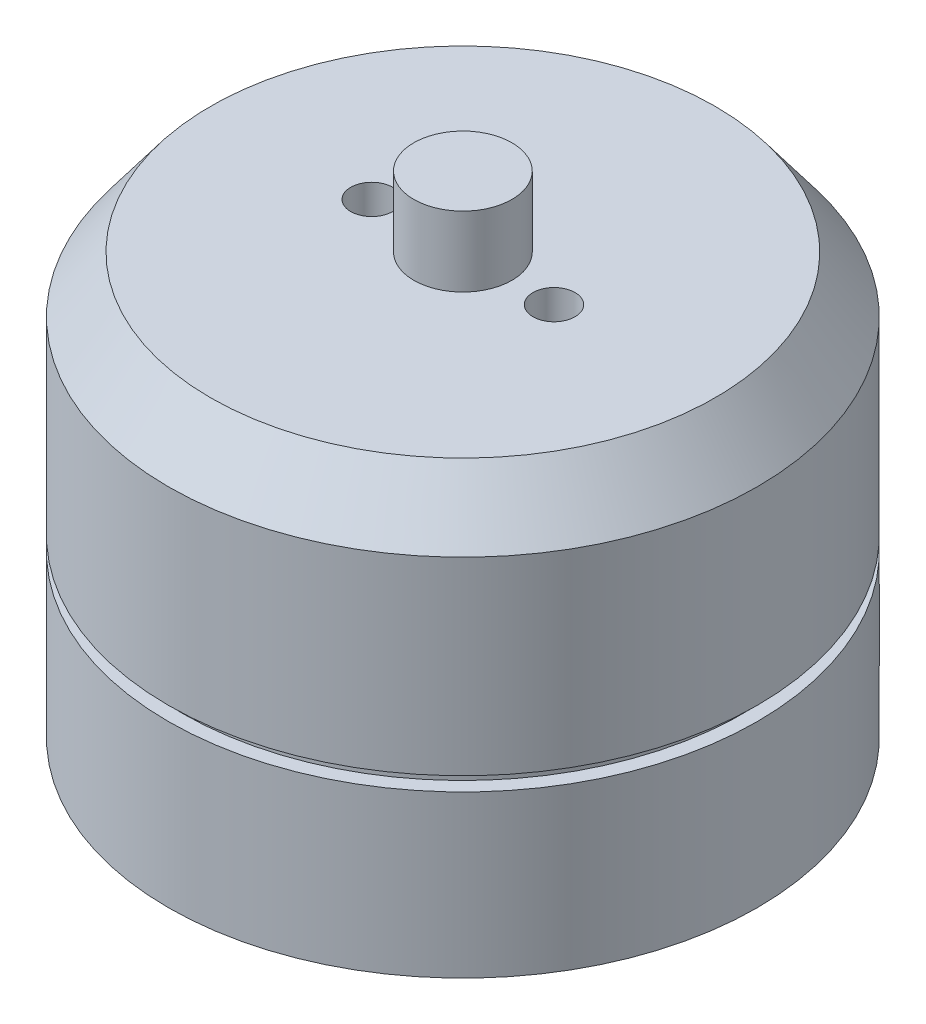
SolidWorks part; units mm, degrees
material "自定义电机"
ref_plane "前视基准面" through (0, 0, 0) normal (0, 0, 1) x (1, 0, 0)
ref_plane "上视基准面" through (0, 0, 0) normal (0, 1, 0) x (1, 0, 0)
ref_plane "右视基准面" through (0, 0, 0) normal (1, 0, 0) x (0, 0, -1)
sketch "草图1" plane through (0, 0, 0) normal (0, 1, 0) x (1, 0, 0)
  circle A0 centre (0, 0) radius 21
extrude "凸台-拉伸1" add sketch "草图1" along normal blind 30
chamfer "倒角1" distance 4 distance2 3 1 edges at (0, 30, 21)
sketch "草图2" plane through (0, 30, 0) normal (0, 1, 0) x (1, 0, 0)
  circle A0 centre (0, 0) radius 3.5
extrude "凸台-拉伸2" add sketch "草图2" along normal blind 5
sketch "草图3" plane through (0, 30, 0) normal (0, 1, 0) x (1, 0, 0)
  circle A0 centre (6.5, 0) radius 1.5
  circle A1 centre (-6.5, 0) radius 1.5
extrude "切除-拉伸1" cut sketch "草图3" against normal blind 4
sketch "草图4" plane through (0, 0, 0) normal (0, -1, 0) x (-1, 0, 0)
  circle A0 centre (0, 0) radius 13.365
  dimension "D1" = 26.73
extrude "凸台-拉伸3" add sketch "草图4" along normal blind 2
sketch "草图5" plane through (0, 0, 0) normal (0, -1, 0) x (-1, 0, 0)
  circle A0 centre (0, 17.5) radius 1.5
  circle A1 centre (17.5, 0) radius 1.5
  circle A2 centre (0, -17.5) radius 1.5
  circle A3 centre (-17.5, 0) radius 1.5
  point P11 (0, 0)
  dimension "D1" = 4
extrude "切除-拉伸2" cut sketch "草图5" against normal blind 4
sketch "草图6" plane through (0, -2, 0) normal (0, -1, 0) x (-1, 0, 0)
  circle A0 centre (0, 0) radius 7.5
extrude "切除-拉伸3" cut sketch "草图6" against normal blind 5
sketch "草图7" plane through (0, 3, 0) normal (0, -1, 0) x (1, 0, 0)
  circle A0 centre (0, 0) radius 2.5
  dimension "D1" = 5
extrude "凸台-拉伸4" add sketch "草图7" along normal blind 12
sketch "草图8" plane through (0, 0, 0) normal (0, 0, 1) x (1, 0, 0)
  line L0 (21, 0) -> (21, 26) construction
  line L1 (21, 12.5) -> (20, 12.5)
  line L2 (21, 12.5) -> (21, 11.5)
  line L3 (21, 11.5) -> (20, 11.5)
  line L4 (20, 12.5) -> (20, 11.5)
  line L5 (18, 30) -> (-18, 30) construction
  point P6 (21, 12)
  dimension "D1" = 1
  dimension "D2" = 1
  dimension "D3" = 18
ref_axis "基准轴1" through (0, 26, 0) along (0, -1, 0)
revolve "切除-旋转1" cut sketch "草图8" angle 360 about axis through (0, 26, 0) along (0, -1, 0)
sketch "草图9" plane through (0, -9, 0) normal (0, -1, 0) x (1, 0, 0)
  arc B0 (3.2715, -4.6677) -> (3.5942, -4.424) centre (0, 0) ccw
  arc B1 (4.7368, -3.1707) -> (4.9496, -2.8269) centre (0, 0) ccw
  arc B2 (5.5623, -1.2455) -> (5.6366, -0.848) centre (0, 0) ccw
  arc B3 (5.6366, 0.848) -> (5.5623, 1.2455) centre (0, 0) ccw
  arc B4 (4.9496, 2.8269) -> (4.7368, 3.1707) centre (0, 0) ccw
  arc B5 (3.5942, 4.424) -> (3.2715, 4.6677) centre (0, 0) ccw
  arc B6 (1.7534, 5.4236) -> (1.3644, 5.5343) centre (0, 0) ccw
  arc B7 (-0.3243, 5.6908) -> (-0.7269, 5.6535) centre (0, 0) ccw
  arc B8 (-2.3581, 5.1893) -> (-2.7201, 5.0091) centre (0, 0) ccw
  arc B9 (-4.0735, 3.9871) -> (-4.3459, 3.6882) centre (0, 0) ccw
  arc B10 (-5.2387, 2.2463) -> (-5.3848, 1.8693) centre (0, 0) ccw
  arc B11 (-5.6964, 0.2022) -> (-5.6964, -0.2022) centre (0, 0) ccw
  arc B12 (-5.3848, -1.8693) -> (-5.2387, -2.2463) centre (0, 0) ccw
  arc B13 (-4.3459, -3.6882) -> (-4.0735, -3.9871) centre (0, 0) ccw
  arc B14 (-2.7201, -5.0091) -> (-2.3581, -5.1893) centre (0, 0) ccw
  arc B15 (-0.7269, -5.6535) -> (-0.3243, -5.6908) centre (0, 0) ccw
  arc B16 (1.3644, -5.5343) -> (1.7534, -5.4236) centre (0, 0) ccw
  spline B17 degree 3 poles (1.7534, -5.4236) (1.767, -5.3721) (1.7863, -5.2911) (1.8073, -5.1815) (1.8206, -5.0976) (1.8304, -5.0184) (1.8372, -4.9441) (1.8413, -4.8747) (1.843, -4.8104) (1.8425, -4.7512) (1.8404, -4.6972) (1.8369, -4.6485) (1.8323, -4.605) (1.827, -4.5667) (1.8213, -4.5337) (1.8156, -4.506) (1.8102, -4.4835) (1.8055, -4.4661) (1.7935, -4.4275) (1.7745, -4.3863) (1.76, -4.3373) (1.7522, -4.3073) (1.7461, -4.2778) (1.7415, -4.2486) (1.7385, -4.2198) (1.7372, -4.1911) (1.7377, -4.1626) (1.7403, -4.1339) (1.7453, -4.1049) (1.7532, -4.0757) (1.7644, -4.046) (1.7797, -4.0163) (1.8, -3.9872) (1.8256, -3.9597) (1.8543, -3.9377) (1.8923, -3.9155) (1.9394, -3.8949) (1.9843, -3.8697) (2.0249, -3.8527) (2.0597, -3.8431) (2.0971, -3.8392) (2.1326, -3.8406) (2.1655, -3.8463) (2.1959, -3.8552) (2.224, -3.8666) (2.2501, -3.88) (2.2746, -3.8952) (2.2977, -3.912) (2.3198, -3.9303) (2.341, -3.9501) (2.3615, -3.9713) (2.3814, -3.9941) (2.4006, -4.0184) (2.431, -4.0595) (2.4524, -4.0994) (2.476, -4.1322) (2.487, -4.1465) (2.5017, -4.1644) (2.5204, -4.1856) (2.5433, -4.21) (2.5706, -4.2373) (2.6026, -4.2672) (2.6394, -4.2994) (2.6812, -4.3336) (2.7282, -4.3696) (2.7805, -4.4071) (2.8383, -4.4456) (2.9017, -4.485) (2.9708, -4.5248) (3.0458, -4.5648) (3.1459, -4.6141) (3.2222, -4.6476) (3.2715, -4.6677) knots 0.010677 0.010677 0.010677 0.010677 0.058365 0.085243 0.110586 0.134392 0.156663 0.177398 0.196597 0.21426 0.230387 0.244978 0.258033 0.269552 0.279536 0.287983 0.294895 0.300271 0.30411 0.331114 0.340625 0.349862 0.358855 0.367643 0.376273 0.384801 0.3933 0.401854 0.410565 0.419553 0.428946 0.438871 0.449424 0.460632 0.472413 0.481614 0.5 0.518386 0.527587 0.539368 0.550576 0.561129 0.571054 0.580447 0.589435 0.598146 0.6067 0.615199 0.623727 0.632357 0.641145 0.650138 0.659375 0.668886 0.69589 0.699729 0.705105 0.712017 0.720464 0.730448 0.741967 0.755022 0.769613 0.78574 0.803403 0.822602 0.843337 0.865608 0.889414 0.914757 0.941635 0.989323 0.989323 0.989323 0.989323
  spline B18 degree 3 poles (3.5942, -4.424) (3.5883, -4.3711) (3.577, -4.2885) (3.557, -4.1787) (3.5391, -4.0957) (3.5197, -4.0183) (3.4992, -3.9466) (3.4779, -3.8804) (3.4562, -3.8198) (3.4345, -3.7648) (3.413, -3.7152) (3.3921, -3.671) (3.3721, -3.6321) (3.3533, -3.5984) (3.3361, -3.5697) (3.3208, -3.5459) (3.3076, -3.5268) (3.2969, -3.5123) (3.2718, -3.4806) (3.2392, -3.4491) (3.208, -3.4086) (3.1899, -3.3835) (3.1735, -3.3581) (3.1586, -3.3326) (3.1454, -3.3068) (3.1339, -3.2806) (3.1241, -3.2537) (3.1162, -3.226) (3.1104, -3.1973) (3.1071, -3.1671) (3.1068, -3.1355) (3.1104, -3.1022) (3.1188, -3.0677) (3.1328, -3.0328) (3.1515, -3.0019) (3.179, -2.9675) (3.2154, -2.9313) (3.2482, -2.8916) (3.2799, -2.8611) (3.3089, -2.8396) (3.3424, -2.8224) (3.376, -2.8109) (3.4087, -2.8043) (3.4403, -2.8016) (3.4706, -2.8021) (3.4998, -2.8052) (3.5281, -2.8105) (3.5557, -2.8178) (3.5829, -2.8269) (3.6099, -2.8377) (3.6366, -2.8501) (3.6634, -2.8641) (3.6901, -2.8798) (3.7333, -2.9072) (3.7676, -2.9366) (3.8015, -2.9588) (3.817, -2.9681) (3.8371, -2.9794) (3.8622, -2.9925) (3.8924, -3.007) (3.9277, -3.0225) (3.9683, -3.0389) (4.0143, -3.0556) (4.0656, -3.0724) (4.1224, -3.089) (4.1848, -3.105) (4.2526, -3.1201) (4.3259, -3.1339) (4.4048, -3.1461) (4.4891, -3.1563) (4.6003, -3.1661) (4.6835, -3.1697) (4.7368, -3.1707) knots 0.010677 0.010677 0.010677 0.010677 0.058365 0.085243 0.110586 0.134392 0.156663 0.177398 0.196597 0.21426 0.230387 0.244978 0.258033 0.269552 0.279536 0.287983 0.294895 0.300271 0.30411 0.331114 0.340625 0.349862 0.358855 0.367643 0.376273 0.384801 0.3933 0.401854 0.410565 0.419553 0.428946 0.438871 0.449424 0.460632 0.472413 0.481614 0.5 0.518386 0.527587 0.539368 0.550576 0.561129 0.571054 0.580447 0.589435 0.598146 0.6067 0.615199 0.623727 0.632357 0.641145 0.650138 0.659375 0.668886 0.69589 0.699729 0.705105 0.712017 0.720464 0.730448 0.741967 0.755022 0.769613 0.78574 0.803403 0.822602 0.843337 0.865608 0.889414 0.914757 0.941635 0.989323 0.989323 0.989323 0.989323
  spline B19 degree 3 poles (4.9496, -2.8269) (4.925, -2.7796) (4.8847, -2.7067) (4.8264, -2.6116) (4.7797, -2.5407) (4.7336, -2.4755) (4.6886, -2.416) (4.6448, -2.362) (4.6027, -2.3134) (4.5625, -2.2699) (4.5246, -2.2314) (4.4891, -2.1978) (4.4564, -2.1687) (4.4267, -2.144) (4.4003, -2.1235) (4.3774, -2.1068) (4.3583, -2.0938) (4.3431, -2.0842) (4.3082, -2.0637) (4.2665, -2.0461) (4.2227, -2.0196) (4.1967, -2.0027) (4.1723, -1.985) (4.1492, -1.9666) (4.1276, -1.9473) (4.1073, -1.927) (4.0885, -1.9055) (4.0711, -1.8825) (4.0553, -1.8578) (4.0414, -1.8309) (4.0297, -1.8014) (4.021, -1.7691) (4.0164, -1.7339) (4.0168, -1.6963) (4.0231, -1.6608) (4.0363, -1.6187) (4.0572, -1.5718) (4.0734, -1.523) (4.092, -1.483) (4.1112, -1.4525) (4.1363, -1.4244) (4.1634, -1.4016) (4.1916, -1.3835) (4.22, -1.3696) (4.2485, -1.3591) (4.2768, -1.3515) (4.3051, -1.3462) (4.3336, -1.3431) (4.3622, -1.3417) (4.3912, -1.342) (4.4206, -1.3439) (4.4506, -1.3473) (4.4812, -1.3523) (4.5314, -1.3622) (4.5741, -1.3773) (4.6137, -1.3857) (4.6314, -1.3888) (4.6543, -1.3921) (4.6825, -1.3952) (4.7158, -1.3978) (4.7544, -1.3996) (4.7981, -1.4001) (4.847, -1.3991) (4.901, -1.3963) (4.96, -1.3912) (5.0238, -1.3837) (5.0925, -1.3732) (5.1659, -1.3596) (5.2438, -1.3425) (5.3261, -1.3215) (5.4333, -1.2905) (5.5123, -1.2638) (5.5623, -1.2455) knots 0.010677 0.010677 0.010677 0.010677 0.058365 0.085243 0.110586 0.134392 0.156663 0.177398 0.196597 0.21426 0.230387 0.244978 0.258033 0.269552 0.279536 0.287983 0.294895 0.300271 0.30411 0.331114 0.340625 0.349862 0.358855 0.367643 0.376273 0.384801 0.3933 0.401854 0.410565 0.419553 0.428946 0.438871 0.449424 0.460632 0.472413 0.481614 0.5 0.518386 0.527587 0.539368 0.550576 0.561129 0.571054 0.580447 0.589435 0.598146 0.6067 0.615199 0.623727 0.632357 0.641145 0.650138 0.659375 0.668886 0.69589 0.699729 0.705105 0.712017 0.720464 0.730448 0.741967 0.755022 0.769613 0.78574 0.803403 0.822602 0.843337 0.865608 0.889414 0.914757 0.941635 0.989323 0.989323 0.989323 0.989323
  spline B20 degree 3 poles (5.6366, -0.848) (5.5966, -0.8128) (5.5326, -0.7594) (5.4439, -0.6917) (5.3747, -0.6425) (5.3082, -0.5984) (5.2447, -0.5592) (5.1844, -0.5246) (5.1276, -0.4944) (5.0744, -0.4684) (5.0251, -0.4463) (4.9799, -0.4277) (4.9389, -0.4124) (4.9023, -0.4001) (4.8703, -0.3905) (4.8429, -0.3832) (4.8203, -0.378) (4.8027, -0.3745) (4.7627, -0.368) (4.7175, -0.3667) (4.6671, -0.3578) (4.6368, -0.3514) (4.6076, -0.3437) (4.5794, -0.3349) (4.5523, -0.3247) (4.5261, -0.3131) (4.5007, -0.2999) (4.4762, -0.2847) (4.4526, -0.2674) (4.4298, -0.2473) (4.4083, -0.2241) (4.3886, -0.1971) (4.3715, -0.166) (4.3583, -0.1307) (4.3514, -0.0953) (4.3485, -0.0514) (4.351, 0) (4.3485, 0.0514) (4.3514, 0.0953) (4.3583, 0.1307) (4.3715, 0.166) (4.3886, 0.1971) (4.4083, 0.2241) (4.4298, 0.2473) (4.4526, 0.2674) (4.4762, 0.2847) (4.5007, 0.2999) (4.5261, 0.3131) (4.5523, 0.3247) (4.5794, 0.3349) (4.6076, 0.3437) (4.6368, 0.3514) (4.6671, 0.3578) (4.7175, 0.3667) (4.7627, 0.368) (4.8027, 0.3745) (4.8203, 0.378) (4.8429, 0.3832) (4.8703, 0.3905) (4.9023, 0.4001) (4.9389, 0.4124) (4.9799, 0.4277) (5.0251, 0.4463) (5.0744, 0.4684) (5.1276, 0.4944) (5.1844, 0.5246) (5.2447, 0.5592) (5.3082, 0.5984) (5.3747, 0.6425) (5.4439, 0.6917) (5.5326, 0.7594) (5.5966, 0.8128) (5.6366, 0.848) knots 0.010677 0.010677 0.010677 0.010677 0.058365 0.085243 0.110586 0.134392 0.156663 0.177398 0.196597 0.21426 0.230387 0.244978 0.258033 0.269552 0.279536 0.287983 0.294895 0.300271 0.30411 0.331114 0.340625 0.349862 0.358855 0.367643 0.376273 0.384801 0.3933 0.401854 0.410565 0.419553 0.428946 0.438871 0.449424 0.460632 0.472413 0.481614 0.5 0.518386 0.527587 0.539368 0.550576 0.561129 0.571054 0.580447 0.589435 0.598146 0.6067 0.615199 0.623727 0.632357 0.641145 0.650138 0.659375 0.668886 0.69589 0.699729 0.705105 0.712017 0.720464 0.730448 0.741967 0.755022 0.769613 0.78574 0.803403 0.822602 0.843337 0.865608 0.889414 0.914757 0.941635 0.989323 0.989323 0.989323 0.989323
  spline B21 degree 3 poles (5.5623, 1.2455) (5.5123, 1.2638) (5.4333, 1.2905) (5.3261, 1.3215) (5.2438, 1.3425) (5.1659, 1.3596) (5.0925, 1.3732) (5.0238, 1.3837) (4.96, 1.3912) (4.901, 1.3963) (4.847, 1.3991) (4.7981, 1.4001) (4.7544, 1.3996) (4.7158, 1.3978) (4.6825, 1.3952) (4.6543, 1.3921) (4.6314, 1.3888) (4.6137, 1.3857) (4.5741, 1.3773) (4.5314, 1.3622) (4.4812, 1.3523) (4.4506, 1.3473) (4.4206, 1.3439) (4.3912, 1.342) (4.3622, 1.3417) (4.3336, 1.3431) (4.3051, 1.3462) (4.2768, 1.3515) (4.2485, 1.3591) (4.22, 1.3696) (4.1916, 1.3835) (4.1634, 1.4016) (4.1363, 1.4244) (4.1112, 1.4525) (4.092, 1.483) (4.0734, 1.523) (4.0572, 1.5718) (4.0363, 1.6187) (4.0231, 1.6608) (4.0168, 1.6963) (4.0164, 1.7339) (4.021, 1.7691) (4.0297, 1.8014) (4.0414, 1.8309) (4.0553, 1.8578) (4.0711, 1.8825) (4.0885, 1.9055) (4.1073, 1.927) (4.1276, 1.9473) (4.1492, 1.9666) (4.1723, 1.985) (4.1967, 2.0027) (4.2227, 2.0196) (4.2665, 2.0461) (4.3082, 2.0637) (4.3431, 2.0842) (4.3583, 2.0938) (4.3774, 2.1068) (4.4003, 2.1235) (4.4267, 2.144) (4.4564, 2.1687) (4.4891, 2.1978) (4.5246, 2.2314) (4.5625, 2.2699) (4.6027, 2.3134) (4.6448, 2.362) (4.6886, 2.416) (4.7336, 2.4755) (4.7797, 2.5407) (4.8264, 2.6116) (4.8847, 2.7067) (4.925, 2.7796) (4.9496, 2.8269) knots 0.010677 0.010677 0.010677 0.010677 0.058365 0.085243 0.110586 0.134392 0.156663 0.177398 0.196597 0.21426 0.230387 0.244978 0.258033 0.269552 0.279536 0.287983 0.294895 0.300271 0.30411 0.331114 0.340625 0.349862 0.358855 0.367643 0.376273 0.384801 0.3933 0.401854 0.410565 0.419553 0.428946 0.438871 0.449424 0.460632 0.472413 0.481614 0.5 0.518386 0.527587 0.539368 0.550576 0.561129 0.571054 0.580447 0.589435 0.598146 0.6067 0.615199 0.623727 0.632357 0.641145 0.650138 0.659375 0.668886 0.69589 0.699729 0.705105 0.712017 0.720464 0.730448 0.741967 0.755022 0.769613 0.78574 0.803403 0.822602 0.843337 0.865608 0.889414 0.914757 0.941635 0.989323 0.989323 0.989323 0.989323
  spline B22 degree 3 poles (4.7368, 3.1707) (4.6835, 3.1697) (4.6003, 3.1661) (4.4891, 3.1563) (4.4048, 3.1461) (4.3259, 3.1339) (4.2526, 3.1201) (4.1848, 3.105) (4.1224, 3.089) (4.0656, 3.0724) (4.0143, 3.0556) (3.9683, 3.0389) (3.9277, 3.0225) (3.8924, 3.007) (3.8622, 2.9925) (3.8371, 2.9794) (3.817, 2.9681) (3.8015, 2.9588) (3.7676, 2.9366) (3.7333, 2.9072) (3.6901, 2.8798) (3.6634, 2.8641) (3.6366, 2.8501) (3.6099, 2.8377) (3.5829, 2.8269) (3.5557, 2.8178) (3.5281, 2.8105) (3.4998, 2.8052) (3.4706, 2.8021) (3.4403, 2.8016) (3.4087, 2.8043) (3.376, 2.8109) (3.3424, 2.8224) (3.3089, 2.8396) (3.2799, 2.8611) (3.2482, 2.8916) (3.2154, 2.9313) (3.179, 2.9675) (3.1515, 3.0019) (3.1328, 3.0328) (3.1188, 3.0677) (3.1104, 3.1022) (3.1068, 3.1355) (3.1071, 3.1671) (3.1104, 3.1973) (3.1162, 3.226) (3.1241, 3.2537) (3.1339, 3.2806) (3.1454, 3.3068) (3.1586, 3.3326) (3.1735, 3.3581) (3.1899, 3.3835) (3.208, 3.4086) (3.2392, 3.4491) (3.2718, 3.4806) (3.2969, 3.5123) (3.3076, 3.5268) (3.3208, 3.5459) (3.3361, 3.5697) (3.3533, 3.5984) (3.3721, 3.6321) (3.3921, 3.671) (3.413, 3.7152) (3.4345, 3.7648) (3.4562, 3.8198) (3.4779, 3.8804) (3.4992, 3.9466) (3.5197, 4.0183) (3.5391, 4.0957) (3.557, 4.1787) (3.577, 4.2885) (3.5883, 4.3711) (3.5942, 4.424) knots 0.010677 0.010677 0.010677 0.010677 0.058365 0.085243 0.110586 0.134392 0.156663 0.177398 0.196597 0.21426 0.230387 0.244978 0.258033 0.269552 0.279536 0.287983 0.294895 0.300271 0.30411 0.331114 0.340625 0.349862 0.358855 0.367643 0.376273 0.384801 0.3933 0.401854 0.410565 0.419553 0.428946 0.438871 0.449424 0.460632 0.472413 0.481614 0.5 0.518386 0.527587 0.539368 0.550576 0.561129 0.571054 0.580447 0.589435 0.598146 0.6067 0.615199 0.623727 0.632357 0.641145 0.650138 0.659375 0.668886 0.69589 0.699729 0.705105 0.712017 0.720464 0.730448 0.741967 0.755022 0.769613 0.78574 0.803403 0.822602 0.843337 0.865608 0.889414 0.914757 0.941635 0.989323 0.989323 0.989323 0.989323
  spline B23 degree 3 poles (3.2715, 4.6677) (3.2222, 4.6476) (3.1459, 4.6141) (3.0458, 4.5648) (2.9708, 4.5248) (2.9017, 4.485) (2.8383, 4.4456) (2.7805, 4.4071) (2.7282, 4.3696) (2.6812, 4.3336) (2.6394, 4.2994) (2.6026, 4.2672) (2.5706, 4.2373) (2.5433, 4.21) (2.5204, 4.1856) (2.5017, 4.1644) (2.487, 4.1465) (2.476, 4.1322) (2.4524, 4.0994) (2.431, 4.0595) (2.4006, 4.0184) (2.3814, 3.9941) (2.3615, 3.9713) (2.341, 3.9501) (2.3198, 3.9303) (2.2977, 3.912) (2.2746, 3.8952) (2.2501, 3.88) (2.224, 3.8666) (2.1959, 3.8552) (2.1655, 3.8463) (2.1326, 3.8406) (2.0971, 3.8392) (2.0597, 3.8431) (2.0249, 3.8527) (1.9843, 3.8697) (1.9394, 3.8949) (1.8923, 3.9155) (1.8543, 3.9377) (1.8256, 3.9597) (1.8, 3.9872) (1.7797, 4.0163) (1.7644, 4.046) (1.7532, 4.0757) (1.7453, 4.1049) (1.7403, 4.1339) (1.7377, 4.1626) (1.7372, 4.1911) (1.7385, 4.2198) (1.7415, 4.2486) (1.7461, 4.2778) (1.7522, 4.3073) (1.76, 4.3373) (1.7745, 4.3863) (1.7935, 4.4275) (1.8055, 4.4661) (1.8102, 4.4835) (1.8156, 4.506) (1.8213, 4.5337) (1.827, 4.5667) (1.8323, 4.605) (1.8369, 4.6485) (1.8404, 4.6972) (1.8425, 4.7512) (1.843, 4.8104) (1.8413, 4.8747) (1.8372, 4.9441) (1.8304, 5.0184) (1.8206, 5.0976) (1.8073, 5.1815) (1.7863, 5.2911) (1.767, 5.3721) (1.7534, 5.4236) knots 0.010677 0.010677 0.010677 0.010677 0.058365 0.085243 0.110586 0.134392 0.156663 0.177398 0.196597 0.21426 0.230387 0.244978 0.258033 0.269552 0.279536 0.287983 0.294895 0.300271 0.30411 0.331114 0.340625 0.349862 0.358855 0.367643 0.376273 0.384801 0.3933 0.401854 0.410565 0.419553 0.428946 0.438871 0.449424 0.460632 0.472413 0.481614 0.5 0.518386 0.527587 0.539368 0.550576 0.561129 0.571054 0.580447 0.589435 0.598146 0.6067 0.615199 0.623727 0.632357 0.641145 0.650138 0.659375 0.668886 0.69589 0.699729 0.705105 0.712017 0.720464 0.730448 0.741967 0.755022 0.769613 0.78574 0.803403 0.822602 0.843337 0.865608 0.889414 0.914757 0.941635 0.989323 0.989323 0.989323 0.989323
  spline B24 degree 3 poles (1.3644, 5.5343) (1.3257, 5.4977) (1.2667, 5.4389) (1.1911, 5.3568) (1.1357, 5.2925) (1.0856, 5.2304) (1.0407, 5.1707) (1.0007, 5.1139) (0.9655, 5.0601) (0.9346, 5.0096) (0.908, 4.9625) (0.8854, 4.9192) (0.8664, 4.8798) (0.8507, 4.8445) (0.8382, 4.8135) (0.8284, 4.7869) (0.8212, 4.7649) (0.8161, 4.7476) (0.8059, 4.7085) (0.8004, 4.6635) (0.7869, 4.6142) (0.7777, 4.5846) (0.7674, 4.5562) (0.756, 4.529) (0.7434, 4.5029) (0.7294, 4.4779) (0.7139, 4.4539) (0.6965, 4.4309) (0.6771, 4.4089) (0.655, 4.3881) (0.6299, 4.3688) (0.6012, 4.3517) (0.5686, 4.3375) (0.5323, 4.3277) (0.4964, 4.324) (0.4524, 4.3252) (0.4015, 4.3324) (0.3501, 4.3347) (0.3066, 4.3416) (0.272, 4.3518) (0.2381, 4.3682) (0.2087, 4.388) (0.1836, 4.4102) (0.1625, 4.4338) (0.1446, 4.4582) (0.1295, 4.4834) (0.1167, 4.5092) (0.1058, 4.5357) (0.0967, 4.5628) (0.0891, 4.5908) (0.0829, 4.6197) (0.0779, 4.6494) (0.0744, 4.6802) (0.0702, 4.7312) (0.073, 4.7764) (0.0702, 4.8167) (0.0684, 4.8347) (0.0653, 4.8576) (0.0606, 4.8855) (0.0539, 4.9183) (0.0451, 4.9559) (0.0336, 4.9981) (0.0193, 5.0449) (0.0018, 5.096) (-0.0192, 5.1513) (-0.044, 5.2107) (-0.0728, 5.2739) (-0.106, 5.3408) (-0.1438, 5.411) (-0.1865, 5.4845) (-0.2457, 5.5791) (-0.2929, 5.6477) (-0.3243, 5.6908) knots 0.010677 0.010677 0.010677 0.010677 0.058365 0.085243 0.110586 0.134392 0.156663 0.177398 0.196597 0.21426 0.230387 0.244978 0.258033 0.269552 0.279536 0.287983 0.294895 0.300271 0.30411 0.331114 0.340625 0.349862 0.358855 0.367643 0.376273 0.384801 0.3933 0.401854 0.410565 0.419553 0.428946 0.438871 0.449424 0.460632 0.472413 0.481614 0.5 0.518386 0.527587 0.539368 0.550576 0.561129 0.571054 0.580447 0.589435 0.598146 0.6067 0.615199 0.623727 0.632357 0.641145 0.650138 0.659375 0.668886 0.69589 0.699729 0.705105 0.712017 0.720464 0.730448 0.741967 0.755022 0.769613 0.78574 0.803403 0.822602 0.843337 0.865608 0.889414 0.914757 0.941635 0.989323 0.989323 0.989323 0.989323
  spline B25 degree 3 poles (-0.7269, 5.6535) (-0.7498, 5.6054) (-0.7837, 5.5292) (-0.8245, 5.4254) (-0.8529, 5.3453) (-0.8771, 5.2693) (-0.8975, 5.1975) (-0.9142, 5.1301) (-0.9277, 5.0672) (-0.9381, 5.0089) (-0.946, 4.9554) (-0.9514, 4.9068) (-0.9549, 4.8632) (-0.9567, 4.8247) (-0.9572, 4.7912) (-0.9567, 4.7629) (-0.9556, 4.7398) (-0.9541, 4.7218) (-0.9494, 4.6816) (-0.9383, 4.6377) (-0.9331, 4.5869) (-0.9309, 4.556) (-0.9303, 4.5258) (-0.9311, 4.4963) (-0.9335, 4.4674) (-0.9375, 4.439) (-0.9433, 4.411) (-0.9511, 4.3833) (-0.9613, 4.3558) (-0.9744, 4.3284) (-0.9909, 4.3014) (-1.0114, 4.275) (-1.0367, 4.25) (-1.067, 4.2277) (-1.0992, 4.2114) (-1.1406, 4.1966) (-1.1907, 4.1849) (-1.2394, 4.1684) (-1.2825, 4.1592) (-1.3185, 4.1562) (-1.3559, 4.1592) (-1.3906, 4.1671) (-1.4219, 4.1787) (-1.4502, 4.193) (-1.4757, 4.2094) (-1.4988, 4.2274) (-1.5201, 4.2469) (-1.5398, 4.2676) (-1.5581, 4.2897) (-1.5753, 4.313) (-1.5916, 4.3376) (-1.6069, 4.3636) (-1.6213, 4.391) (-1.6437, 4.4371) (-1.6574, 4.4802) (-1.6746, 4.5168) (-1.6827, 4.5329) (-1.6939, 4.5532) (-1.7084, 4.5775) (-1.7264, 4.6057) (-1.7483, 4.6375) (-1.7742, 4.6727) (-1.8044, 4.7112) (-1.8392, 4.7525) (-1.8788, 4.7965) (-1.9234, 4.843) (-1.9731, 4.8915) (-2.0282, 4.9418) (-2.0888, 4.9937) (-2.1551, 5.0467) (-2.2445, 5.1136) (-2.3133, 5.1605) (-2.3581, 5.1893) knots 0.010677 0.010677 0.010677 0.010677 0.058365 0.085243 0.110586 0.134392 0.156663 0.177398 0.196597 0.21426 0.230387 0.244978 0.258033 0.269552 0.279536 0.287983 0.294895 0.300271 0.30411 0.331114 0.340625 0.349862 0.358855 0.367643 0.376273 0.384801 0.3933 0.401854 0.410565 0.419553 0.428946 0.438871 0.449424 0.460632 0.472413 0.481614 0.5 0.518386 0.527587 0.539368 0.550576 0.561129 0.571054 0.580447 0.589435 0.598146 0.6067 0.615199 0.623727 0.632357 0.641145 0.650138 0.659375 0.668886 0.69589 0.699729 0.705105 0.712017 0.720464 0.730448 0.741967 0.755022 0.769613 0.78574 0.803403 0.822602 0.843337 0.865608 0.889414 0.914757 0.941635 0.989323 0.989323 0.989323 0.989323
  spline B26 degree 3 poles (-2.7201, 5.0091) (-2.7241, 4.956) (-2.7281, 4.8728) (-2.7286, 4.7612) (-2.7263, 4.6763) (-2.7214, 4.5966) (-2.7144, 4.5223) (-2.7057, 4.4534) (-2.6955, 4.3899) (-2.6842, 4.3318) (-2.6722, 4.2791) (-2.6597, 4.2318) (-2.6472, 4.1899) (-2.635, 4.1533) (-2.6234, 4.1219) (-2.6127, 4.0957) (-2.6032, 4.0745) (-2.5954, 4.0583) (-2.5765, 4.0225) (-2.5503, 3.9856) (-2.527, 3.9401) (-2.5139, 3.912) (-2.5024, 3.8841) (-2.4925, 3.8563) (-2.4842, 3.8285) (-2.4777, 3.8006) (-2.473, 3.7724) (-2.4703, 3.7437) (-2.4699, 3.7143) (-2.4722, 3.6841) (-2.4778, 3.653) (-2.4874, 3.6209) (-2.502, 3.5886) (-2.5221, 3.5568) (-2.5462, 3.5299) (-2.5796, 3.5011) (-2.6221, 3.4722) (-2.6615, 3.4392) (-2.6983, 3.4151) (-2.7308, 3.3992) (-2.7669, 3.3885) (-2.802, 3.3834) (-2.8354, 3.3829) (-2.8669, 3.386) (-2.8966, 3.3921) (-2.9248, 3.4005) (-2.9516, 3.411) (-2.9774, 3.4232) (-3.0025, 3.4371) (-3.027, 3.4527) (-3.051, 3.4698) (-3.0747, 3.4885) (-3.0981, 3.5088) (-3.1355, 3.5437) (-3.1639, 3.5789) (-3.1931, 3.6069) (-3.2066, 3.6189) (-3.2243, 3.6338) (-3.2466, 3.6512) (-3.2736, 3.671) (-3.3055, 3.6928) (-3.3424, 3.7163) (-3.3845, 3.7412) (-3.4318, 3.7672) (-3.4846, 3.7939) (-3.543, 3.8211) (-3.6069, 3.8484) (-3.6764, 3.8754) (-3.7517, 3.9019) (-3.8327, 3.9274) (-3.9402, 3.9575) (-4.0213, 3.9763) (-4.0735, 3.9871) knots 0.010677 0.010677 0.010677 0.010677 0.058365 0.085243 0.110586 0.134392 0.156663 0.177398 0.196597 0.21426 0.230387 0.244978 0.258033 0.269552 0.279536 0.287983 0.294895 0.300271 0.30411 0.331114 0.340625 0.349862 0.358855 0.367643 0.376273 0.384801 0.3933 0.401854 0.410565 0.419553 0.428946 0.438871 0.449424 0.460632 0.472413 0.481614 0.5 0.518386 0.527587 0.539368 0.550576 0.561129 0.571054 0.580447 0.589435 0.598146 0.6067 0.615199 0.623727 0.632357 0.641145 0.650138 0.659375 0.668886 0.69589 0.699729 0.705105 0.712017 0.720464 0.730448 0.741967 0.755022 0.769613 0.78574 0.803403 0.822602 0.843337 0.865608 0.889414 0.914757 0.941635 0.989323 0.989323 0.989323 0.989323
  spline B27 degree 3 poles (-4.3459, 3.6882) (-4.3304, 3.6373) (-4.3041, 3.5582) (-4.2643, 3.454) (-4.2314, 3.3757) (-4.1981, 3.3032) (-4.1648, 3.2364) (-4.1317, 3.1753) (-4.0993, 3.1197) (-4.0678, 3.0696) (-4.0375, 3.0248) (-4.0088, 2.9852) (-3.982, 2.9506) (-3.9574, 2.9209) (-3.9352, 2.8959) (-3.9158, 2.8753) (-3.8993, 2.859) (-3.8861, 2.8467) (-3.8556, 2.8202) (-3.8179, 2.7952) (-3.7797, 2.7611) (-3.7573, 2.7397) (-3.7365, 2.7178) (-3.7172, 2.6955) (-3.6995, 2.6726) (-3.6833, 2.6489) (-3.6688, 2.6243) (-3.6559, 2.5985) (-3.6449, 2.5713) (-3.6361, 2.5423) (-3.6301, 2.5112) (-3.6275, 2.4779) (-3.6294, 2.4424) (-3.6367, 2.4055) (-3.6495, 2.3717) (-3.6701, 2.3329) (-3.6993, 2.2905) (-3.7242, 2.2455) (-3.7498, 2.2097) (-3.7743, 2.1832) (-3.8041, 2.1602) (-3.835, 2.1427) (-3.866, 2.1302) (-3.8965, 2.1217) (-3.9264, 2.1167) (-3.9557, 2.1144) (-3.9845, 2.1144) (-4.013, 2.1165) (-4.0414, 2.1204) (-4.0698, 2.126) (-4.0984, 2.1333) (-4.1273, 2.1422) (-4.1564, 2.1527) (-4.2039, 2.1717) (-4.2431, 2.1943) (-4.2805, 2.2098) (-4.2973, 2.2162) (-4.3193, 2.2236) (-4.3464, 2.2319) (-4.3787, 2.2406) (-4.4163, 2.2494) (-4.4592, 2.2579) (-4.5074, 2.266) (-4.561, 2.2731) (-4.6199, 2.2789) (-4.6841, 2.2832) (-4.7535, 2.2856) (-4.8281, 2.2857) (-4.9079, 2.2832) (-4.9926, 2.2777) (-5.1037, 2.2669) (-5.1862, 2.2552) (-5.2387, 2.2463) knots 0.010677 0.010677 0.010677 0.010677 0.058365 0.085243 0.110586 0.134392 0.156663 0.177398 0.196597 0.21426 0.230387 0.244978 0.258033 0.269552 0.279536 0.287983 0.294895 0.300271 0.30411 0.331114 0.340625 0.349862 0.358855 0.367643 0.376273 0.384801 0.3933 0.401854 0.410565 0.419553 0.428946 0.438871 0.449424 0.460632 0.472413 0.481614 0.5 0.518386 0.527587 0.539368 0.550576 0.561129 0.571054 0.580447 0.589435 0.598146 0.6067 0.615199 0.623727 0.632357 0.641145 0.650138 0.659375 0.668886 0.69589 0.699729 0.705105 0.712017 0.720464 0.730448 0.741967 0.755022 0.769613 0.78574 0.803403 0.822602 0.843337 0.865608 0.889414 0.914757 0.941635 0.989323 0.989323 0.989323 0.989323
  spline B28 degree 3 poles (-5.3848, 1.8693) (-5.3519, 1.8273) (-5.2989, 1.7631) (-5.2241, 1.6803) (-5.1651, 1.6191) (-5.1079, 1.5636) (-5.0527, 1.5133) (-4.9998, 1.4683) (-4.9494, 1.4282) (-4.902, 1.3929) (-4.8576, 1.362) (-4.8165, 1.3355) (-4.779, 1.3129) (-4.7453, 1.2941) (-4.7156, 1.2787) (-4.69, 1.2666) (-4.6688, 1.2573) (-4.6521, 1.2506) (-4.614, 1.2369) (-4.5698, 1.2273) (-4.5219, 1.2093) (-4.4933, 1.1974) (-4.466, 1.1845) (-4.4399, 1.1707) (-4.4151, 1.1557) (-4.3915, 1.1394) (-4.369, 1.1218) (-4.3477, 1.1024) (-4.3276, 1.081) (-4.309, 1.0571) (-4.2921, 1.0303) (-4.2776, 1.0001) (-4.2666, 0.9664) (-4.2601, 0.9293) (-4.2598, 0.8932) (-4.265, 0.8495) (-4.2769, 0.7995) (-4.2839, 0.7486) (-4.2948, 0.7059) (-4.3081, 0.6723) (-4.3276, 0.6401) (-4.3501, 0.6127) (-4.3744, 0.5898) (-4.3999, 0.5709) (-4.4259, 0.5553) (-4.4523, 0.5426) (-4.4792, 0.5323) (-4.5065, 0.5239) (-4.5345, 0.5173) (-4.563, 0.5123) (-4.5923, 0.5087) (-4.6224, 0.5066) (-4.6534, 0.5059) (-4.7045, 0.5064) (-4.7493, 0.5134) (-4.7897, 0.5143) (-4.8077, 0.5141) (-4.8309, 0.5132) (-4.8591, 0.5111) (-4.8924, 0.5075) (-4.9306, 0.5021) (-4.9737, 0.4946) (-5.0216, 0.4847) (-5.0741, 0.472) (-5.1311, 0.4562) (-5.1925, 0.437) (-5.2582, 0.4141) (-5.3278, 0.3872) (-5.4012, 0.3561) (-5.4783, 0.3203) (-5.578, 0.2701) (-5.6506, 0.2294) (-5.6964, 0.2022) knots 0.010677 0.010677 0.010677 0.010677 0.058365 0.085243 0.110586 0.134392 0.156663 0.177398 0.196597 0.21426 0.230387 0.244978 0.258033 0.269552 0.279536 0.287983 0.294895 0.300271 0.30411 0.331114 0.340625 0.349862 0.358855 0.367643 0.376273 0.384801 0.3933 0.401854 0.410565 0.419553 0.428946 0.438871 0.449424 0.460632 0.472413 0.481614 0.5 0.518386 0.527587 0.539368 0.550576 0.561129 0.571054 0.580447 0.589435 0.598146 0.6067 0.615199 0.623727 0.632357 0.641145 0.650138 0.659375 0.668886 0.69589 0.699729 0.705105 0.712017 0.720464 0.730448 0.741967 0.755022 0.769613 0.78574 0.803403 0.822602 0.843337 0.865608 0.889414 0.914757 0.941635 0.989323 0.989323 0.989323 0.989323
  spline B29 degree 3 poles (-5.6964, -0.2022) (-5.6506, -0.2294) (-5.578, -0.2701) (-5.4783, -0.3203) (-5.4012, -0.3561) (-5.3278, -0.3872) (-5.2582, -0.4141) (-5.1925, -0.437) (-5.1311, -0.4562) (-5.0741, -0.472) (-5.0216, -0.4847) (-4.9737, -0.4946) (-4.9306, -0.5021) (-4.8924, -0.5075) (-4.8591, -0.5111) (-4.8309, -0.5132) (-4.8077, -0.5141) (-4.7897, -0.5143) (-4.7493, -0.5134) (-4.7045, -0.5064) (-4.6534, -0.5059) (-4.6224, -0.5066) (-4.5923, -0.5087) (-4.563, -0.5123) (-4.5345, -0.5173) (-4.5065, -0.5239) (-4.4792, -0.5323) (-4.4523, -0.5426) (-4.4259, -0.5553) (-4.3999, -0.5709) (-4.3744, -0.5898) (-4.3501, -0.6127) (-4.3276, -0.6401) (-4.3081, -0.6723) (-4.2948, -0.7059) (-4.2839, -0.7486) (-4.2769, -0.7995) (-4.265, -0.8495) (-4.2598, -0.8932) (-4.2601, -0.9293) (-4.2666, -0.9664) (-4.2776, -1.0001) (-4.2921, -1.0303) (-4.309, -1.0571) (-4.3276, -1.081) (-4.3477, -1.1024) (-4.369, -1.1218) (-4.3915, -1.1394) (-4.4151, -1.1557) (-4.4399, -1.1707) (-4.466, -1.1845) (-4.4933, -1.1974) (-4.5219, -1.2093) (-4.5698, -1.2273) (-4.614, -1.2369) (-4.6521, -1.2506) (-4.6688, -1.2573) (-4.69, -1.2666) (-4.7156, -1.2787) (-4.7453, -1.2941) (-4.779, -1.3129) (-4.8165, -1.3355) (-4.8576, -1.362) (-4.902, -1.3929) (-4.9494, -1.4282) (-4.9998, -1.4683) (-5.0527, -1.5133) (-5.1079, -1.5636) (-5.1651, -1.6191) (-5.2241, -1.6803) (-5.2989, -1.7631) (-5.3519, -1.8273) (-5.3848, -1.8693) knots 0.010677 0.010677 0.010677 0.010677 0.058365 0.085243 0.110586 0.134392 0.156663 0.177398 0.196597 0.21426 0.230387 0.244978 0.258033 0.269552 0.279536 0.287983 0.294895 0.300271 0.30411 0.331114 0.340625 0.349862 0.358855 0.367643 0.376273 0.384801 0.3933 0.401854 0.410565 0.419553 0.428946 0.438871 0.449424 0.460632 0.472413 0.481614 0.5 0.518386 0.527587 0.539368 0.550576 0.561129 0.571054 0.580447 0.589435 0.598146 0.6067 0.615199 0.623727 0.632357 0.641145 0.650138 0.659375 0.668886 0.69589 0.699729 0.705105 0.712017 0.720464 0.730448 0.741967 0.755022 0.769613 0.78574 0.803403 0.822602 0.843337 0.865608 0.889414 0.914757 0.941635 0.989323 0.989323 0.989323 0.989323
  spline B30 degree 3 poles (-5.2387, -2.2463) (-5.1862, -2.2552) (-5.1037, -2.2669) (-4.9926, -2.2777) (-4.9079, -2.2832) (-4.8281, -2.2857) (-4.7535, -2.2856) (-4.6841, -2.2832) (-4.6199, -2.2789) (-4.561, -2.2731) (-4.5074, -2.266) (-4.4592, -2.2579) (-4.4163, -2.2494) (-4.3787, -2.2406) (-4.3464, -2.2319) (-4.3193, -2.2236) (-4.2973, -2.2162) (-4.2805, -2.2098) (-4.2431, -2.1943) (-4.2039, -2.1717) (-4.1564, -2.1527) (-4.1273, -2.1422) (-4.0984, -2.1333) (-4.0698, -2.126) (-4.0414, -2.1204) (-4.013, -2.1165) (-3.9845, -2.1144) (-3.9557, -2.1144) (-3.9264, -2.1167) (-3.8965, -2.1217) (-3.866, -2.1302) (-3.835, -2.1427) (-3.8041, -2.1602) (-3.7743, -2.1832) (-3.7498, -2.2097) (-3.7242, -2.2455) (-3.6993, -2.2905) (-3.6701, -2.3329) (-3.6495, -2.3717) (-3.6367, -2.4055) (-3.6294, -2.4424) (-3.6275, -2.4779) (-3.6301, -2.5112) (-3.6361, -2.5423) (-3.6449, -2.5713) (-3.6559, -2.5985) (-3.6688, -2.6243) (-3.6833, -2.6489) (-3.6995, -2.6726) (-3.7172, -2.6955) (-3.7365, -2.7178) (-3.7573, -2.7397) (-3.7797, -2.7611) (-3.8179, -2.7952) (-3.8556, -2.8202) (-3.8861, -2.8467) (-3.8993, -2.859) (-3.9158, -2.8753) (-3.9352, -2.8959) (-3.9574, -2.9209) (-3.982, -2.9506) (-4.0088, -2.9852) (-4.0375, -3.0248) (-4.0678, -3.0696) (-4.0993, -3.1197) (-4.1317, -3.1753) (-4.1648, -3.2364) (-4.1981, -3.3032) (-4.2314, -3.3757) (-4.2643, -3.454) (-4.3041, -3.5582) (-4.3304, -3.6373) (-4.3459, -3.6882) knots 0.010677 0.010677 0.010677 0.010677 0.058365 0.085243 0.110586 0.134392 0.156663 0.177398 0.196597 0.21426 0.230387 0.244978 0.258033 0.269552 0.279536 0.287983 0.294895 0.300271 0.30411 0.331114 0.340625 0.349862 0.358855 0.367643 0.376273 0.384801 0.3933 0.401854 0.410565 0.419553 0.428946 0.438871 0.449424 0.460632 0.472413 0.481614 0.5 0.518386 0.527587 0.539368 0.550576 0.561129 0.571054 0.580447 0.589435 0.598146 0.6067 0.615199 0.623727 0.632357 0.641145 0.650138 0.659375 0.668886 0.69589 0.699729 0.705105 0.712017 0.720464 0.730448 0.741967 0.755022 0.769613 0.78574 0.803403 0.822602 0.843337 0.865608 0.889414 0.914757 0.941635 0.989323 0.989323 0.989323 0.989323
  spline B31 degree 3 poles (-4.0735, -3.9871) (-4.0213, -3.9763) (-3.9402, -3.9575) (-3.8327, -3.9274) (-3.7517, -3.9019) (-3.6764, -3.8754) (-3.6069, -3.8484) (-3.543, -3.8211) (-3.4846, -3.7939) (-3.4318, -3.7672) (-3.3845, -3.7412) (-3.3424, -3.7163) (-3.3055, -3.6928) (-3.2736, -3.671) (-3.2466, -3.6512) (-3.2243, -3.6338) (-3.2066, -3.6189) (-3.1931, -3.6069) (-3.1639, -3.5789) (-3.1355, -3.5437) (-3.0981, -3.5088) (-3.0747, -3.4885) (-3.051, -3.4698) (-3.027, -3.4527) (-3.0025, -3.4371) (-2.9774, -3.4232) (-2.9516, -3.411) (-2.9248, -3.4005) (-2.8966, -3.3921) (-2.8669, -3.386) (-2.8354, -3.3829) (-2.802, -3.3834) (-2.7669, -3.3885) (-2.7308, -3.3992) (-2.6983, -3.4151) (-2.6615, -3.4392) (-2.6221, -3.4722) (-2.5796, -3.5011) (-2.5462, -3.5299) (-2.5221, -3.5568) (-2.502, -3.5886) (-2.4874, -3.6209) (-2.4778, -3.653) (-2.4722, -3.6841) (-2.4699, -3.7143) (-2.4703, -3.7437) (-2.473, -3.7724) (-2.4777, -3.8006) (-2.4842, -3.8285) (-2.4925, -3.8563) (-2.5024, -3.8841) (-2.5139, -3.912) (-2.527, -3.9401) (-2.5503, -3.9856) (-2.5765, -4.0225) (-2.5954, -4.0583) (-2.6032, -4.0745) (-2.6127, -4.0957) (-2.6234, -4.1219) (-2.635, -4.1533) (-2.6472, -4.1899) (-2.6597, -4.2318) (-2.6722, -4.2791) (-2.6842, -4.3318) (-2.6955, -4.3899) (-2.7057, -4.4534) (-2.7144, -4.5223) (-2.7214, -4.5966) (-2.7263, -4.6763) (-2.7286, -4.7612) (-2.7281, -4.8728) (-2.7241, -4.956) (-2.7201, -5.0091) knots 0.010677 0.010677 0.010677 0.010677 0.058365 0.085243 0.110586 0.134392 0.156663 0.177398 0.196597 0.21426 0.230387 0.244978 0.258033 0.269552 0.279536 0.287983 0.294895 0.300271 0.30411 0.331114 0.340625 0.349862 0.358855 0.367643 0.376273 0.384801 0.3933 0.401854 0.410565 0.419553 0.428946 0.438871 0.449424 0.460632 0.472413 0.481614 0.5 0.518386 0.527587 0.539368 0.550576 0.561129 0.571054 0.580447 0.589435 0.598146 0.6067 0.615199 0.623727 0.632357 0.641145 0.650138 0.659375 0.668886 0.69589 0.699729 0.705105 0.712017 0.720464 0.730448 0.741967 0.755022 0.769613 0.78574 0.803403 0.822602 0.843337 0.865608 0.889414 0.914757 0.941635 0.989323 0.989323 0.989323 0.989323
  spline B32 degree 3 poles (-2.3581, -5.1893) (-2.3133, -5.1605) (-2.2445, -5.1136) (-2.1551, -5.0467) (-2.0888, -4.9937) (-2.0282, -4.9418) (-1.9731, -4.8915) (-1.9234, -4.843) (-1.8788, -4.7965) (-1.8392, -4.7525) (-1.8044, -4.7112) (-1.7742, -4.6727) (-1.7483, -4.6375) (-1.7264, -4.6057) (-1.7084, -4.5775) (-1.6939, -4.5532) (-1.6827, -4.5329) (-1.6746, -4.5168) (-1.6574, -4.4802) (-1.6437, -4.4371) (-1.6213, -4.391) (-1.6069, -4.3636) (-1.5916, -4.3376) (-1.5753, -4.313) (-1.5581, -4.2897) (-1.5398, -4.2676) (-1.5201, -4.2469) (-1.4988, -4.2274) (-1.4757, -4.2094) (-1.4502, -4.193) (-1.4219, -4.1787) (-1.3906, -4.1671) (-1.3559, -4.1592) (-1.3185, -4.1562) (-1.2825, -4.1592) (-1.2394, -4.1684) (-1.1907, -4.1849) (-1.1406, -4.1966) (-1.0992, -4.2114) (-1.067, -4.2277) (-1.0367, -4.25) (-1.0114, -4.275) (-0.9909, -4.3014) (-0.9744, -4.3284) (-0.9613, -4.3558) (-0.9511, -4.3833) (-0.9433, -4.411) (-0.9375, -4.439) (-0.9335, -4.4674) (-0.9311, -4.4963) (-0.9303, -4.5258) (-0.9309, -4.556) (-0.9331, -4.5869) (-0.9383, -4.6377) (-0.9494, -4.6816) (-0.9541, -4.7218) (-0.9556, -4.7398) (-0.9567, -4.7629) (-0.9572, -4.7912) (-0.9567, -4.8247) (-0.9549, -4.8632) (-0.9514, -4.9068) (-0.946, -4.9554) (-0.9381, -5.0089) (-0.9277, -5.0672) (-0.9142, -5.1301) (-0.8975, -5.1975) (-0.8771, -5.2693) (-0.8529, -5.3453) (-0.8245, -5.4254) (-0.7837, -5.5292) (-0.7498, -5.6054) (-0.7269, -5.6535) knots 0.010677 0.010677 0.010677 0.010677 0.058365 0.085243 0.110586 0.134392 0.156663 0.177398 0.196597 0.21426 0.230387 0.244978 0.258033 0.269552 0.279536 0.287983 0.294895 0.300271 0.30411 0.331114 0.340625 0.349862 0.358855 0.367643 0.376273 0.384801 0.3933 0.401854 0.410565 0.419553 0.428946 0.438871 0.449424 0.460632 0.472413 0.481614 0.5 0.518386 0.527587 0.539368 0.550576 0.561129 0.571054 0.580447 0.589435 0.598146 0.6067 0.615199 0.623727 0.632357 0.641145 0.650138 0.659375 0.668886 0.69589 0.699729 0.705105 0.712017 0.720464 0.730448 0.741967 0.755022 0.769613 0.78574 0.803403 0.822602 0.843337 0.865608 0.889414 0.914757 0.941635 0.989323 0.989323 0.989323 0.989323
  spline B33 degree 3 poles (-0.3243, -5.6908) (-0.2929, -5.6477) (-0.2457, -5.5791) (-0.1865, -5.4845) (-0.1438, -5.411) (-0.106, -5.3408) (-0.0728, -5.2739) (-0.044, -5.2107) (-0.0192, -5.1513) (0.0018, -5.096) (0.0193, -5.0449) (0.0336, -4.9981) (0.0451, -4.9559) (0.0539, -4.9183) (0.0606, -4.8855) (0.0653, -4.8576) (0.0684, -4.8347) (0.0702, -4.8167) (0.073, -4.7764) (0.0702, -4.7312) (0.0744, -4.6802) (0.0779, -4.6494) (0.0829, -4.6197) (0.0891, -4.5908) (0.0967, -4.5628) (0.1058, -4.5357) (0.1167, -4.5092) (0.1295, -4.4834) (0.1446, -4.4582) (0.1625, -4.4338) (0.1836, -4.4102) (0.2087, -4.388) (0.2381, -4.3682) (0.272, -4.3518) (0.3066, -4.3416) (0.3501, -4.3347) (0.4015, -4.3324) (0.4524, -4.3252) (0.4964, -4.324) (0.5323, -4.3277) (0.5686, -4.3375) (0.6012, -4.3517) (0.6299, -4.3688) (0.655, -4.3881) (0.6771, -4.4089) (0.6965, -4.4309) (0.7139, -4.4539) (0.7294, -4.4779) (0.7434, -4.5029) (0.756, -4.529) (0.7674, -4.5562) (0.7777, -4.5846) (0.7869, -4.6142) (0.8004, -4.6635) (0.8059, -4.7085) (0.8161, -4.7476) (0.8212, -4.7649) (0.8284, -4.7869) (0.8382, -4.8135) (0.8507, -4.8445) (0.8664, -4.8798) (0.8854, -4.9192) (0.908, -4.9625) (0.9346, -5.0096) (0.9655, -5.0601) (1.0007, -5.1139) (1.0407, -5.1707) (1.0856, -5.2304) (1.1357, -5.2925) (1.1911, -5.3568) (1.2667, -5.4389) (1.3257, -5.4977) (1.3644, -5.5343) knots 0.010677 0.010677 0.010677 0.010677 0.058365 0.085243 0.110586 0.134392 0.156663 0.177398 0.196597 0.21426 0.230387 0.244978 0.258033 0.269552 0.279536 0.287983 0.294895 0.300271 0.30411 0.331114 0.340625 0.349862 0.358855 0.367643 0.376273 0.384801 0.3933 0.401854 0.410565 0.419553 0.428946 0.438871 0.449424 0.460632 0.472413 0.481614 0.5 0.518386 0.527587 0.539368 0.550576 0.561129 0.571054 0.580447 0.589435 0.598146 0.6067 0.615199 0.623727 0.632357 0.641145 0.650138 0.659375 0.668886 0.69589 0.699729 0.705105 0.712017 0.720464 0.730448 0.741967 0.755022 0.769613 0.78574 0.803403 0.822602 0.843337 0.865608 0.889414 0.914757 0.941635 0.989323 0.989323 0.989323 0.989323
sketch_block_instance "块1-1"
sketch_block "块1"
extrude "凸台-拉伸5" add sketch "草图9" against normal up to surface (7 mm away) up to face at (0, -2, -7.5)
ref_plane "基准面1" through (0, 0, -25) normal (0, 0, 1) x (1, 0, 0)
sketch "草图10" plane through (0, 0, -25) normal (0, 0, 1) x (1, 0, 0)
  line L0 (0, 26) -> (0, 0) construction
  line L1 (15, 4.8) -> (-15, 4.8)
  line L2 (15, 4.8) -> (15, 9.55)
  line L3 (15, 9.55) -> (-15, 9.55)
  line L4 (-15, 4.8) -> (-15, 9.55)
  line L5 (0, 9.55) -> (0, 4.8) construction
  line L6 (15, 7.175) -> (-15, 7.175) construction
  line L7 (-21, 0) -> (21, 0) construction
  point P0 (0, 7.175)
  dimension "D1" = 30
  dimension "D2" = 4.8
  dimension "D3" = 4.75
extrude "切除-拉伸4" cut sketch "草图10" along normal blind 14
